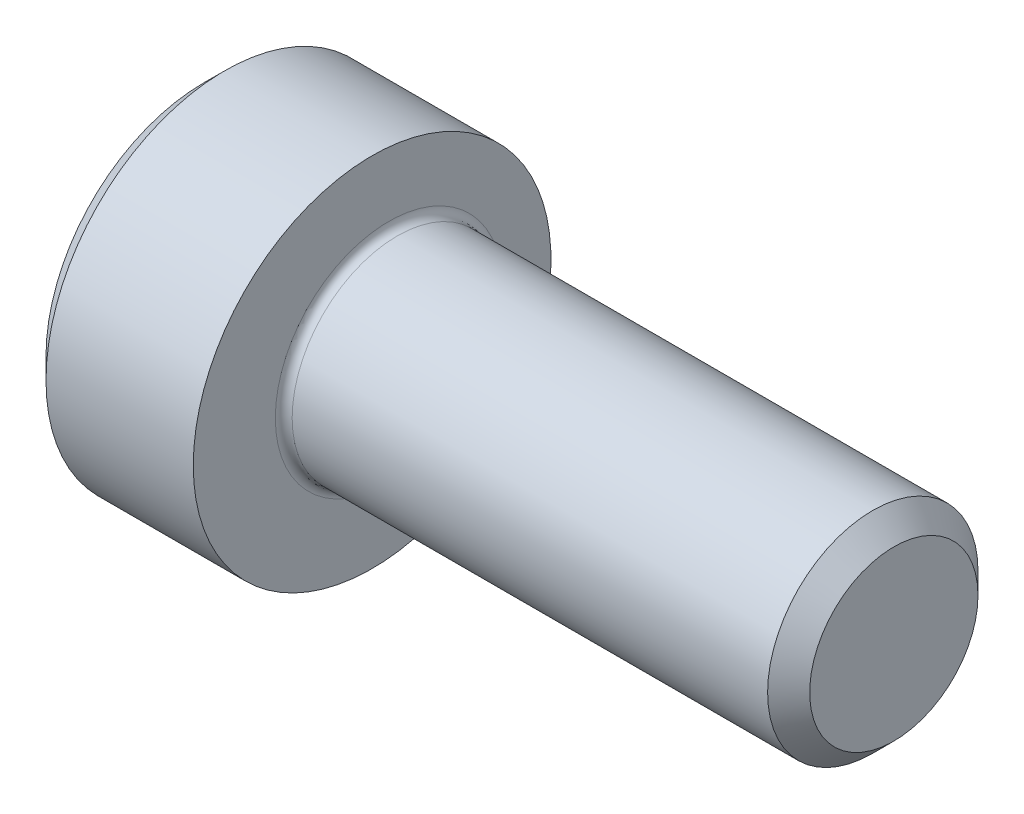
SolidWorks part; units mm, degrees
material "Galvanized Steel"
ref_plane "Plano frontal" through (0, 0, 0) normal (0, 0, 1) x (1, 0, 0)
ref_plane "Plano superior" through (0, 0, 0) normal (0, 1, 0) x (1, 0, 0)
ref_plane "Plano direito" through (0, 0, 0) normal (1, 0, 0) x (0, 0, -1)
ref_plane "Plano1" through (0, 0, 0) normal (0, 0, -1) x (-1, 0, 0)
sketch "Esboço1" plane through (0, 0, 0) normal (0, 0, -1) x (-1, 0, 0)
  line L0 (-4, 4.25) -> (-4, 0)
  line L1 (-4, 0) -> (0, 0)
  line L2 (0, 0) -> (0, 4.25)
  line L3 (0, 4.25) -> (-4, 4.25)
  line L4 (-4, 0) -> (0, 0) construction
  dimension "D1" = 4
  dimension "D2" = 4.25
revolve "Revolução1" add sketch "Esboço1" angle 360 about L4
sketch "Esboço2" plane through (4, 0, 0) normal (1, 0, 0) x (0, 0, -1)
  line L0 (0, 0) -> (0.4, 0) construction
  circle A0 centre (0.4, 0) radius 2.5
  dimension "D1" = 5
  dimension "D2" = 0.4
extrude "Ressalto-extrusão1" add sketch "Esboço2" along normal blind 12
sketch "Esboço3" plane through (0, 0, 0) normal (-1, 0, 0) x (0, 0, 1)
  line L0 (0, -2.3579) -> (2.042, -1.1789)
  line L1 (2.042, -1.1789) -> (2.042, 1.1789)
  line L2 (2.042, 1.1789) -> (0, 2.3579)
  line L3 (0, 2.3579) -> (-2.042, 1.1789)
  line L4 (-2.042, 1.1789) -> (-2.042, -1.1789)
  line L5 (-2.042, -1.1789) -> (0, -2.3579)
extrude "Corte-extrusão1" cut sketch "Esboço3" against normal blind 2.5
sketch "Esboço4" plane through (0, 0, 0) normal (0, 0, 1) x (1, 0, 0)
  line L0 (2.5, 2.042) -> (2.5, 0)
  line L1 (2.5, 0) -> (3.6789, 0)
  line L2 (3.6789, 0) -> (2.5, 2.042)
  line L3 (2.5, 0) -> (3.6789, 0) construction
revolve "Corte-Revolução1" cut sketch "Esboço4" angle 360 about L3
chamfer "Chanfro1" distance 0.5 angle 45 2 edges at (16, 0, -2.9) (0, 0, 4.25)
fillet "Filete1" radius 0.2 1 edges at (4, 0, -2.9)
sketch "Sketch1" plane through (0, 0, 0) normal (-1, 0, 0) x (0, 0, 1)
  line L0 (0, 0) -> (2.8, 0) construction
  circle A0 centre (2.8, 0) radius 0.25
  circle A1 centre (0, 0) radius 2.8 construction
  dimension "D1" = 0.5
  dimension "D2" = 2.8
extrude "Cut-Extrude1" cut sketch "Sketch1" against normal blind 0.2
